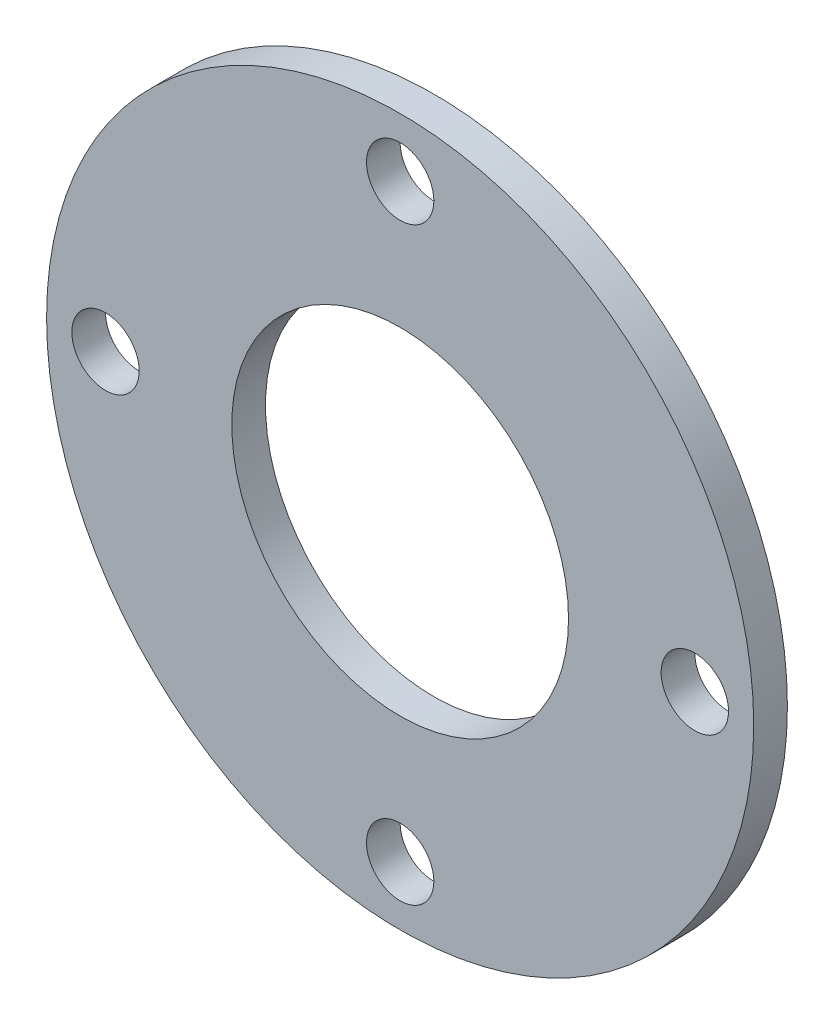
SolidWorks part; units mm, degrees
material "环氧树脂,未充填"
ref_plane "前视基准面" through (0, 0, 0) normal (0, 0, 1) x (1, 0, 0)
ref_plane "上视基准面" through (0, 0, 0) normal (0, 1, 0) x (1, 0, 0)
ref_plane "右视基准面" through (0, 0, 0) normal (1, 0, 0) x (0, 0, -1)
sketch "草图1" plane through (0, 0, 0) normal (0, 0, 1) x (1, 0, 0)
  circle A0 centre (0, 0) radius 10
  circle A1 centre (0, 0) radius 21
  circle A2 centre (0, 0) radius 17.5 construction
  circle A3 centre (0, 17.5) radius 2
  circle A4 centre (-17.5, 0) radius 2
  circle A5 centre (0, -17.5) radius 2
  circle A6 centre (17.5, 0) radius 2
  point P14 (0, 0)
  point P15 (0, 0)
  dimension "D1" = 20
  dimension "D2" = 35
  dimension "D3" = 4
  dimension "D4" = 42
extrude "凸台-拉伸1" add sketch "草图1" along normal blind 2
